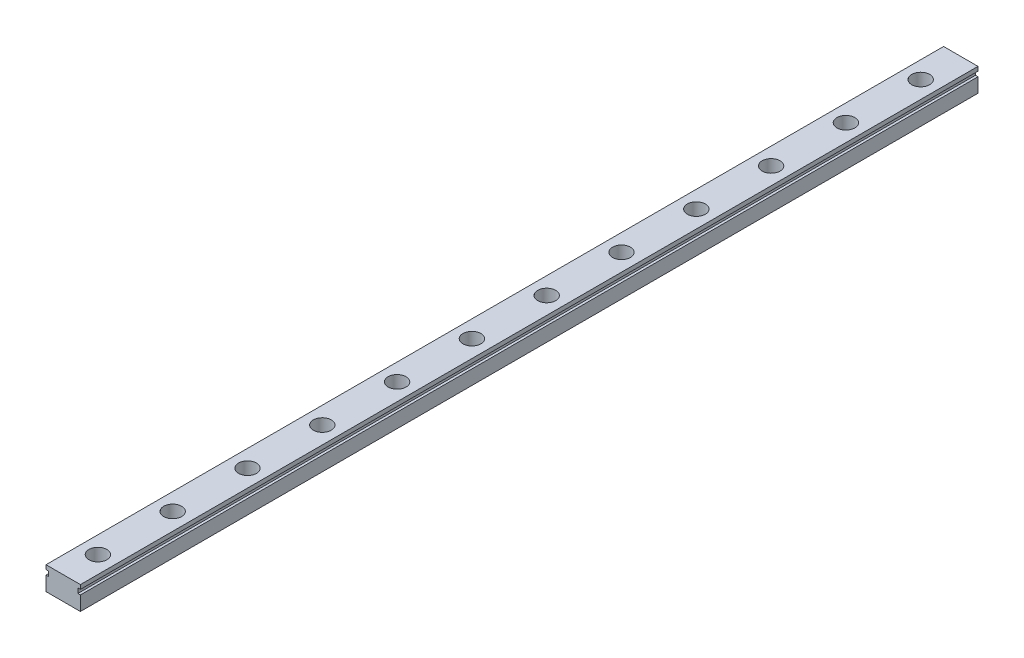
SolidWorks part; units mm, degrees
ref_plane "Front Plane" through (0, 0, 0) normal (0, 0, 1) x (1, 0, 0)
ref_plane "Top Plane" through (0, 0, 0) normal (0, 1, 0) x (1, 0, 0)
ref_plane "Right Plane" through (0, 0, 0) normal (1, 0, 0) x (0, 0, -1)
sketch "Sketch1" plane through (0, 0, 0) normal (0, 0, 1) x (1, 0, 0)
  line L1 (-5.75, -3.9) -> (5.75, -3.9)
  line L2 (-5.75, -3.9) -> (-5.75, 3.9)
  line L3 (-5.75, 3.9) -> (5.75, 3.9)
  line L4 (5.75, -3.9) -> (5.75, 3.9)
  line L5 (-5.75, -3.9) -> (5.75, 3.9) construction
  line L6 (-5.75, 3.9) -> (5.75, -3.9) construction
  point P0 (0, 0)
  dimension "D1" = 11.5
  dimension "D2" = 7.8
extrude "Boss-Extrude1" add sketch "Sketch1" along normal blind 300
sketch "Sketch2" plane through (0, 0, 300) normal (0, 0, 1) x (1, 0, 0)
  line L0 (5.75, -3.9) -> (5.75, 3.9) construction
  line L1 (5.75, 2.5) -> (4.9147, 2.5)
  line L2 (5.75, 2.5) -> (5.75, 0.9)
  line L3 (5.75, 0.9) -> (4.9147, 0.9)
  line L4 (4.9147, 2.5) -> (4.9147, 0.9)
  line L5 (5.75, 3.9) -> (-5.75, 3.9) construction
  line L7 (0, -55) -> (0, 55) construction
  line L8 (-5.75, 0.9) -> (-4.9147, 0.9)
  line L9 (-4.9147, 2.5) -> (-4.9147, 0.9)
  line L10 (-5.75, 2.5) -> (-4.9147, 2.5)
  line L11 (-5.75, 2.5) -> (-5.75, 0.9)
  dimension "D1" = 1.4
  dimension "D2" = 1.6
extrude "Cut-Extrude1" cut sketch "Sketch2" against normal through all
sketch "Sketch3" plane through (0, 3.9, 0) normal (0, 1, 0) x (1, 0, 0)
  line L0 (0, -223.2) -> (0, -215.9183) construction
  line L2 (5.75, -300) -> (-5.75, -300) construction
  circle A0 centre (0, -288.4) radius 3
  circle A1 centre (0, -263.4) radius 3
  circle A2 centre (0, -238.4) radius 3
  circle A3 centre (0, -213.4) radius 3
  circle A4 centre (0, -188.4) radius 3
  circle A5 centre (0, -163.4) radius 3
  circle A6 centre (0, -138.4) radius 3
  circle A7 centre (0, -113.4) radius 3
  circle A8 centre (0, -88.4) radius 3
  circle A9 centre (0, -63.4) radius 3
  circle A10 centre (0, -38.4) radius 3
  circle A11 centre (0, -13.4) radius 3
  circle A12 centre (0, 11.6) radius 3
  circle A13 centre (0, 36.6) radius 3
  circle A14 centre (0, 61.6) radius 3
  circle A15 centre (0, 86.6) radius 3
  circle A16 centre (0, 111.6) radius 3
  circle A17 centre (0, 136.6) radius 3
  circle A18 centre (0, 161.6) radius 3
  circle A19 centre (0, 186.6) radius 3
  circle A20 centre (0, 211.6) radius 3
  circle A21 centre (0, 236.6) radius 3
  circle A22 centre (0, 261.6) radius 3
  circle A23 centre (0, 286.6) radius 3
  circle A24 centre (0, 311.6) radius 3
  circle A25 centre (0, 336.6) radius 3
  circle A26 centre (0, 361.6) radius 3
  circle A27 centre (0, 386.6) radius 3
  circle A28 centre (0, 411.6) radius 3
  circle A29 centre (0, 436.6) radius 3
  dimension "D1" = 11.6
  dimension "D2" = 6
  dimension "D3" = 30
extrude "Cut-Extrude2" cut sketch "Sketch3" against normal blind 4.7
sketch "Sketch4" plane through (0, -0.8, 0) normal (0, 1, 0) x (1, 0, 0)
  circle A0 centre (0, -288.4) radius 1.7
  circle A1 centre (0, -263.4) radius 1.7
  circle A2 centre (0, -238.4) radius 1.7
  circle A3 centre (0, -213.4) radius 1.7
  circle A4 centre (0, -188.4) radius 1.7
  circle A5 centre (0, -163.4) radius 1.7
  circle A6 centre (0, -138.4) radius 1.7
  circle A7 centre (0, -113.4) radius 1.7
  circle A8 centre (0, -88.4) radius 1.7
  circle A9 centre (0, -63.4) radius 1.7
  circle A10 centre (0, -38.4) radius 1.7
  circle A11 centre (0, -13.4) radius 1.7
  circle A12 centre (0, 11.6) radius 1.7
  circle A13 centre (0, 36.6) radius 1.7
  circle A14 centre (0, 61.6) radius 1.7
  circle A15 centre (0, 86.6) radius 1.7
  circle A16 centre (0, 111.6) radius 1.7
  circle A17 centre (0, 136.6) radius 1.7
  circle A18 centre (0, 161.6) radius 1.7
  circle A19 centre (0, 186.6) radius 1.7
  circle A20 centre (0, 211.6) radius 1.7
  circle A21 centre (0, 236.6) radius 1.7
  circle A22 centre (0, 261.6) radius 1.7
  circle A23 centre (0, 286.6) radius 1.7
  circle A24 centre (0, 311.6) radius 1.7
  circle A25 centre (0, 336.6) radius 1.7
  circle A26 centre (0, 361.6) radius 1.7
  circle A27 centre (0, 386.6) radius 1.7
  circle A28 centre (0, 411.6) radius 1.7
  circle A29 centre (0, 436.6) radius 1.7
  dimension "D1" = 3.4
  dimension "D2" = 30
extrude "Cut-Extrude3" cut sketch "Sketch4" against normal through all
